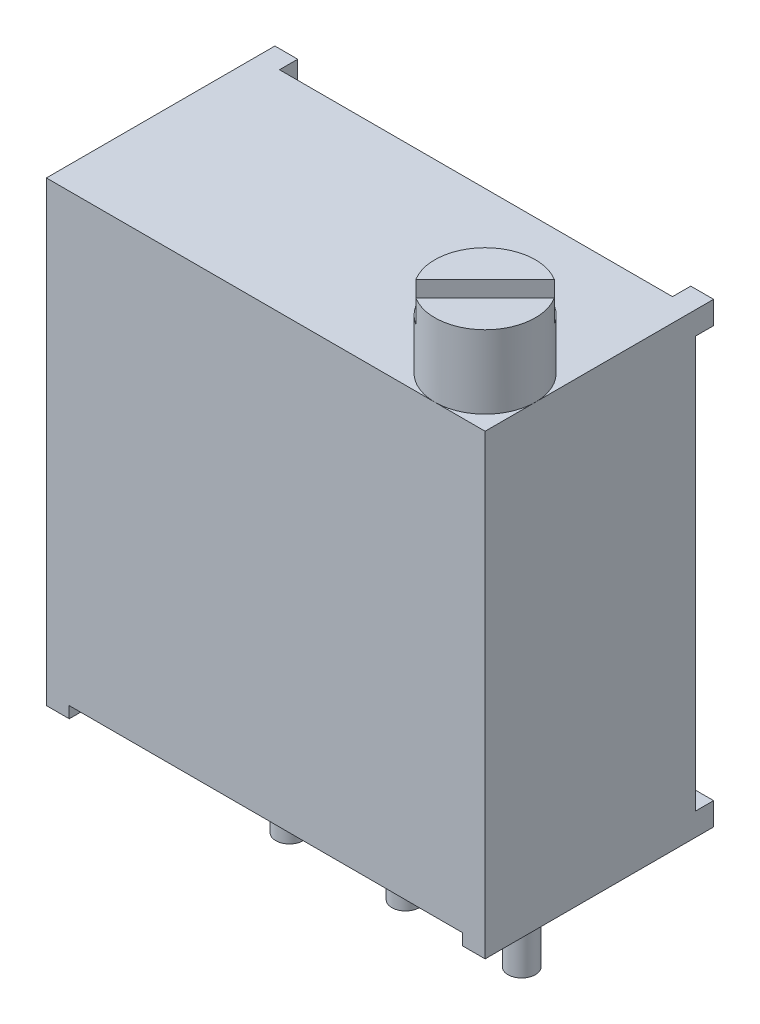
SolidWorks part; units mm, degrees
ref_plane "Front Plane" through (0, 0, 0) normal (0, 0, 1) x (1, 0, 0)
ref_plane "Top Plane" through (0, 0, 0) normal (0, 1, 0) x (1, 0, 0)
ref_plane "Right Plane" through (0, 0, 0) normal (1, 0, 0) x (0, 0, -1)
sketch "Component_Outline" plane through (0, 0, 0) normal (0, 1, 0) x (1, 0, 0)
  line L1 (2.2, 2) -> (-7.4, 2)
  line L2 (2.2, 2) -> (2.2, -3)
  line L3 (2.2, -3) -> (-7.4, -3)
  line L4 (-7.4, 2) -> (-7.4, -3)
  dimension "D1" = 5
  dimension "D2" = 9.6
  dimension "D3" = 3
  dimension "D4" = 2.2
sketch3d "3DSketch1"
  line L0 (0, 0, 0) -> (1, 0, 0)
  line L1 (0, 0, 0) -> (0, 0, -1)
  line L2 (0, 0, 0) -> (0, 1, 0)
  point P0 (0, 0, 0)
extrude "Boss-Extrude1" add sketch "Component_Outline" along normal blind 10
sketch "Sketch1" plane through (0, 0, -2) normal (0, 0, -1) x (-1, 0, 0)
  line L1 (7.4, 10) -> (6.9, 10)
  line L2 (7.4, 10) -> (7.4, 9.5)
  line L3 (7.4, 9.5) -> (6.9, 9.5)
  line L4 (6.9, 10) -> (6.9, 9.5)
  line L5 (-2.2, 10) -> (-1.7, 10)
  line L6 (-2.2, 10) -> (-2.2, 9.5)
  line L7 (-2.2, 9.5) -> (-1.7, 9.5)
  line L8 (-1.7, 10) -> (-1.7, 9.5)
  line L9 (-2.2, 0) -> (-1.7, 0)
  line L10 (-2.2, 0) -> (-2.2, 0.5)
  line L11 (-2.2, 0.5) -> (-1.7, 0.5)
  line L12 (-1.7, 0) -> (-1.7, 0.5)
  line L13 (7.4, 0) -> (6.9, 0)
  line L14 (7.4, 0) -> (7.4, 0.5)
  line L15 (7.4, 0.5) -> (6.9, 0.5)
  line L16 (6.9, 0) -> (6.9, 0.5)
  dimension "D1" = 0.5
extrude "Cut-Extrude1" cut sketch "Sketch1" against normal blind 0.4 flip side to cut
sketch "Sketch2" plane through (0, 0, 0) normal (0, -1, 0) x (1, 0, 0)
  line L0 (-7.4, 3) -> (2.2, 3) construction
  line L1 (-6.9, -1.6) -> (1.7, -1.6)
  line L2 (-6.9, -1.6) -> (-6.9, 3)
  line L3 (-6.9, 3) -> (1.7, 3)
  line L4 (1.7, -1.6) -> (1.7, 3)
extrude "Cut-Extrude2" cut sketch "Sketch2" against normal blind 0.25
sketch "Sketch3" plane through (0, 0.25, 0) normal (0, -1, 0) x (1, 0, 0)
  line L0 (0, 0) -> (-2.54, 0) construction
  line L1 (-2.54, 0) -> (-5.08, 0) construction
  circle A0 centre (0, 0) radius 0.3
  circle A1 centre (-2.54, 0) radius 0.3
  circle A2 centre (-5.08, 0) radius 0.3
  dimension "D1" = 0.6
  dimension "D2" = 2.54
extrude "Boss-Extrude2" add sketch "Sketch3" along normal blind 3
sketch "Sketch4" plane through (0, 10, 0) normal (0, 1, 0) x (1, 0, 0)
  line L0 (-7.4, -3) -> (2.2, -3) construction
  line L1 (2.2, -3) -> (2.2, 2) construction
  circle A0 centre (1.1, -1.9) radius 1.1
  dimension "D1" = 2.2
extrude "Boss-Extrude3" add sketch "Sketch4" along normal blind 1.6 separate body
sketch "Sketch5" plane through (0, 11.6, 0) normal (0, 1, 0) x (1, 0, 0)
  line L0 (1.1, -1.9) -> (1.8778, -1.1222) construction
  line L1 (1.1, -1.9) -> (0.3222, -2.6778) construction
  line L2 (1.1, -1.9) -> (2.2, -1.9) construction
  line L3 (0.1658, -2.4807) -> (1.6807, -0.9658)
  line L4 (2.0342, -1.3193) -> (0.5193, -2.8342)
  circle A0 centre (1.1, -1.9) radius 1.1 construction
  arc A1 (0.1658, -2.4807) -> (0.5193, -2.8342) centre (1.1, -1.9) ccw
  arc A2 (2.0342, -1.3193) -> (1.6807, -0.9658) centre (1.1, -1.9) ccw
  dimension "D1" = 45
  dimension "D2" = 0.5
extrude "Cut-Extrude3" cut sketch "Sketch5" against normal blind 0.5
